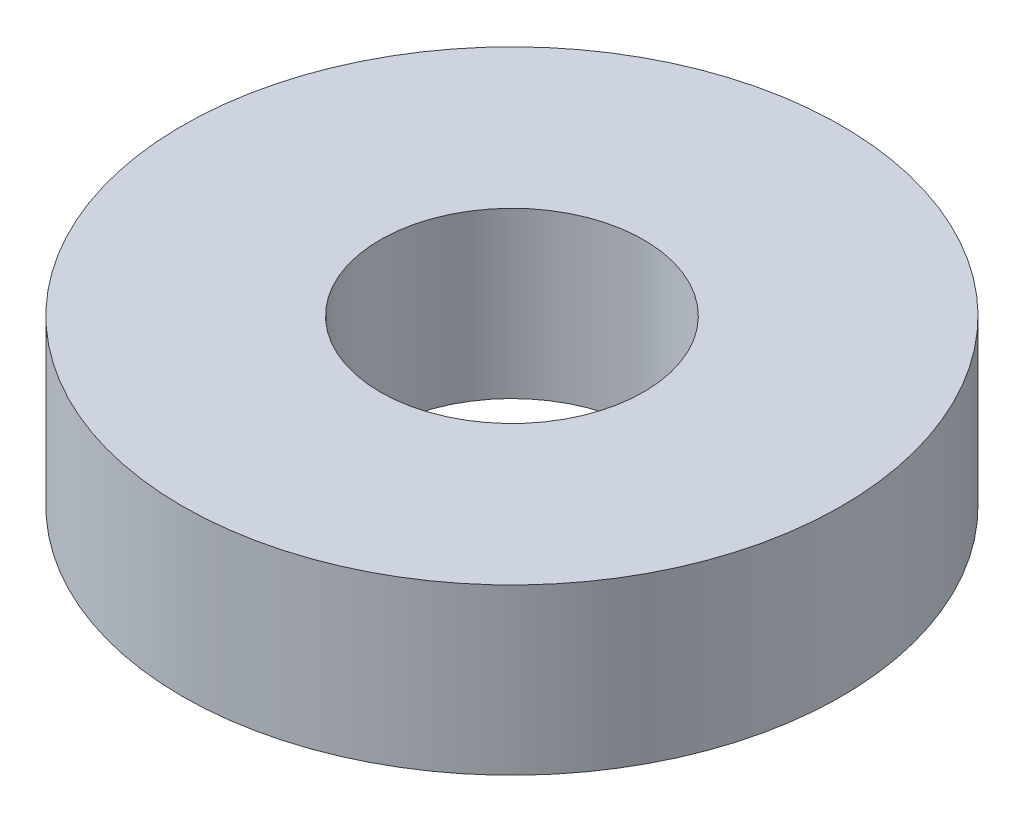
SolidWorks part; units mm, degrees
material "PETG"
ref_plane "Front Plane" through (0, 0, 0) normal (0, 0, 1) x (1, 0, 0)
ref_plane "Top Plane" through (0, 0, 0) normal (0, 1, 0) x (1, 0, 0)
ref_plane "Right Plane" through (0, 0, 0) normal (1, 0, 0) x (0, 0, -1)
sketch "Sketch1" plane through (0, 0, 0) normal (0, 1, 0) x (1, 0, 0)
  circle A0 centre (0, 0) radius 2
  circle A1 centre (0, 0) radius 5
  dimension "D1" = 4
  dimension "D2" = 10
extrude "Boss-Extrude1" add sketch "Sketch1" along normal blind 2.5
